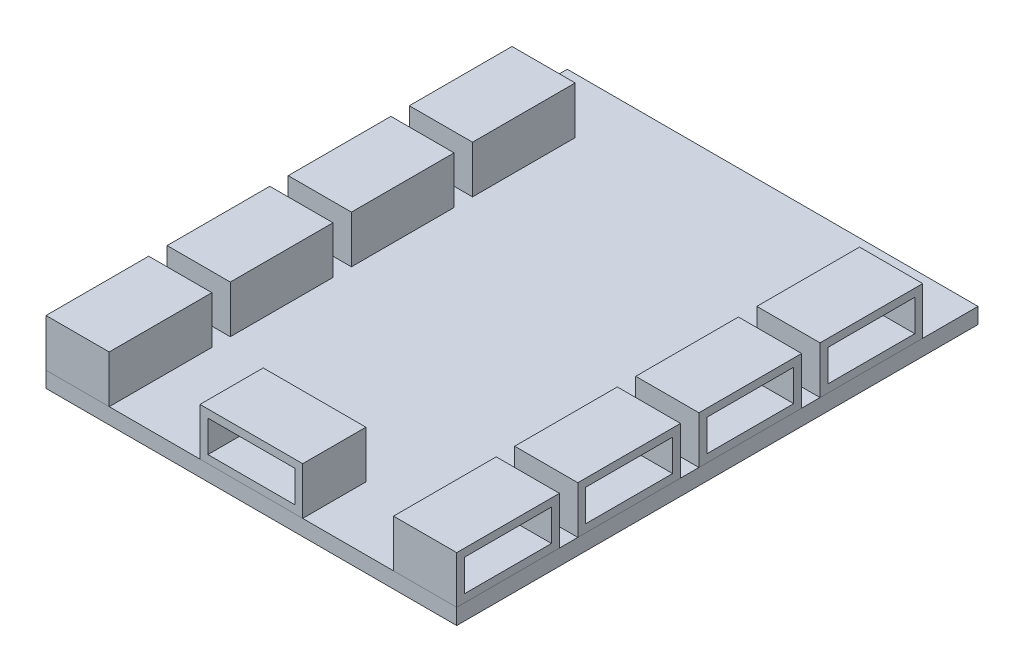
SolidWorks part; units mm, degrees
ref_plane "Front Plane" through (0, 0, 0) normal (0, 0, 1) x (1, 0, 0)
ref_plane "Top Plane" through (0, 0, 0) normal (0, 1, 0) x (1, 0, 0)
ref_plane "Right Plane" through (0, 0, 0) normal (1, 0, 0) x (0, 0, -1)
sketch "Sketch1" plane through (0, 0, 0) normal (0, 1, 0) x (1, 0, 0)
  line L1 (-13, -16.5) -> (13, -16.5)
  line L2 (-13, -16.5) -> (-13, 16.5)
  line L3 (-13, 16.5) -> (13, 16.5)
  line L4 (13, -16.5) -> (13, 16.5)
  line L5 (-13, -16.5) -> (13, 16.5) construction
  line L6 (-13, 16.5) -> (13, -16.5) construction
  point P0 (0, 0)
  dimension "D1" = 26
  dimension "D2" = 33
extrude "Boss-Extrude1" add sketch "Sketch1" along normal blind 1
sketch "Sketch2" plane through (0, 1, 0) normal (0, 1, 0) x (1, 0, 0)
  line L0 (13, 16.5) -> (-13, 16.5) construction
  line L1 (9, 13) -> (13, 13)
  line L2 (9, 13) -> (9, 6.5)
  line L3 (9, 6.5) -> (13, 6.5)
  line L4 (13, 13) -> (13, 6.5)
  line L5 (13, -16.5) -> (13, 16.5) construction
  line L6 (0, 16.5) -> (0, -16.5) construction
  line L7 (-13, -16.5) -> (13, -16.5) construction
  line L8 (9, 5.3333) -> (9, -1.1667)
  line L9 (9, 5.3333) -> (13, 5.3333)
  line L10 (13, 5.3333) -> (13, -1.1667)
  line L11 (9, -1.1667) -> (13, -1.1667)
  line L12 (9, -2.3333) -> (9, -8.8333)
  line L13 (9, -2.3333) -> (13, -2.3333)
  line L14 (13, -2.3333) -> (13, -8.8333)
  line L15 (9, -8.8333) -> (13, -8.8333)
  line L16 (9, -10) -> (9, -16.5)
  line L17 (9, -10) -> (13, -10)
  line L18 (13, -10) -> (13, -16.5)
  line L19 (9, -16.5) -> (13, -16.5)
  line L20 (-9, -10) -> (-13, -10)
  line L21 (-13, -10) -> (-13, -16.5)
  line L22 (-9, -16.5) -> (-13, -16.5)
  line L23 (-9, -10) -> (-9, -16.5)
  line L24 (-9, -2.3333) -> (-13, -2.3333)
  line L25 (-13, -2.3333) -> (-13, -8.8333)
  line L26 (-9, -8.8333) -> (-13, -8.8333)
  line L27 (-9, -2.3333) -> (-9, -8.8333)
  line L28 (-9, 5.3333) -> (-13, 5.3333)
  line L29 (-13, 5.3333) -> (-13, -1.1667)
  line L30 (-9, -1.1667) -> (-13, -1.1667)
  line L31 (-9, 5.3333) -> (-9, -1.1667)
  line L32 (-9, 6.5) -> (-13, 6.5)
  line L33 (-13, 13) -> (-13, 6.5)
  line L34 (-9, 13) -> (-13, 13)
  line L35 (-9, 13) -> (-9, 6.5)
  dimension "D1" = 4
  dimension "D2" = 6.5
  dimension "D3" = 3.5
  dimension "D4" = 4
extrude "Boss-Extrude2" add sketch "Sketch2" along normal blind 3 separate body
sketch "Sketch3" plane through (13, 0, 0) normal (1, 0, 0) x (0, 0, -1)
  line L0 (9.75, 4) -> (9.75, 1) construction
  line L1 (6.5, 4) -> (13, 4) construction
  line L2 (6.5, 1) -> (13, 1) construction
  line L3 (6.5, 2.5) -> (13, 2.5) construction
  line L4 (6.5, 4) -> (6.5, 1) construction
  line L5 (13, 4) -> (13, 1) construction
  line L6 (4.8333, 1.5) -> (4.8333, 3.5)
  line L7 (12.5, 1.5) -> (7, 1.5)
  line L8 (12.5, 1.5) -> (12.5, 3.5)
  line L9 (12.5, 3.5) -> (7, 3.5)
  line L10 (7, 1.5) -> (7, 3.5)
  line L11 (12.5, 1.5) -> (7, 3.5) construction
  line L12 (12.5, 3.5) -> (7, 1.5) construction
  line L13 (4.8333, 1.5) -> (-0.6667, 1.5)
  line L14 (-0.6667, 1.5) -> (-0.6667, 3.5)
  line L15 (4.8333, 3.5) -> (-0.6667, 3.5)
  line L16 (-2.8333, 1.5) -> (-2.8333, 3.5)
  line L17 (-2.8333, 1.5) -> (-8.3333, 1.5)
  line L18 (-8.3333, 1.5) -> (-8.3333, 3.5)
  line L19 (-2.8333, 3.5) -> (-8.3333, 3.5)
  line L20 (-10.5, 1.5) -> (-10.5, 3.5)
  line L21 (-10.5, 1.5) -> (-16, 1.5)
  line L22 (-16, 1.5) -> (-16, 3.5)
  line L23 (-10.5, 3.5) -> (-16, 3.5)
  line L24 (-13.25, 4) -> (-13.25, 1) construction
  line L25 (-16.5, 4) -> (-10, 4) construction
  line L26 (-16.5, 1) -> (-10, 1) construction
  line L27 (-16.5, 2.5) -> (-10, 2.5) construction
  line L28 (-16.5, 4) -> (-16.5, 1) construction
  line L29 (-10, 4) -> (-10, 1) construction
  line L30 (-16, 3.5) -> (-10.5, 1.5) construction
  line L31 (-16, 1.5) -> (-10.5, 3.5) construction
  point P12 (9.75, 2.5)
  point P41 (-13.25, 2.5)
  point P42 (-13.25, 2.5)
  dimension "D1" = 0.5
  dimension "D2" = 0.5
  dimension "D3" = 4
extrude "Cut-Extrude1" cut sketch "Sketch3" against normal blind 3.5
mirror "Mirror1" about plane through (0, 0, 0) normal (1, 0, 0) of "Cut-Extrude1"
sketch "Sketch4" plane through (0, 0, 16.5) normal (0, 0, 1) x (1, 0, 0)
  line L0 (0, 0) -> (0, 7.4579) construction
  line L1 (-13, 0) -> (13, 0) construction
  line L2 (-13, 1) -> (13, 1) construction
  line L3 (3.25, 1) -> (-3.25, 1)
  line L4 (3.25, 1) -> (3.25, 4)
  line L5 (3.25, 4) -> (-3.25, 4)
  line L6 (-3.25, 1) -> (-3.25, 4)
  line L7 (3.25, 1) -> (-3.25, 4) construction
  line L8 (3.25, 4) -> (-3.25, 1) construction
  line L9 (-13, 4) -> (-9, 4) construction
  point P4 (0, 2.5)
  dimension "D1" = 6.5
extrude "Boss-Extrude3" add sketch "Sketch4" against normal blind 4 separate body
sketch "Sketch5" plane through (0, 0, 16.5) normal (0, 0, 1) x (1, 0, 0)
  line L0 (0, 0) -> (0, 4) construction
  line L1 (3.25, 4) -> (-3.25, 4) construction
  line L2 (-3.25, 2.5) -> (3.25, 2.5) construction
  line L3 (-3.25, 4) -> (-3.25, 1) construction
  line L4 (3.25, 1) -> (3.25, 4) construction
  line L6 (-2.75, 3.5) -> (2.75, 3.5)
  line L7 (-2.75, 3.5) -> (-2.75, 1.5)
  line L8 (-2.75, 1.5) -> (2.75, 1.5)
  line L9 (2.75, 3.5) -> (2.75, 1.5)
  line L10 (-2.75, 3.5) -> (2.75, 1.5) construction
  line L11 (-2.75, 1.5) -> (2.75, 3.5) construction
  point P11 (0, 2.5)
  dimension "D1" = 0.5
  dimension "D2" = 0.5
extrude "Cut-Extrude2" cut sketch "Sketch5" against normal blind 3.5
